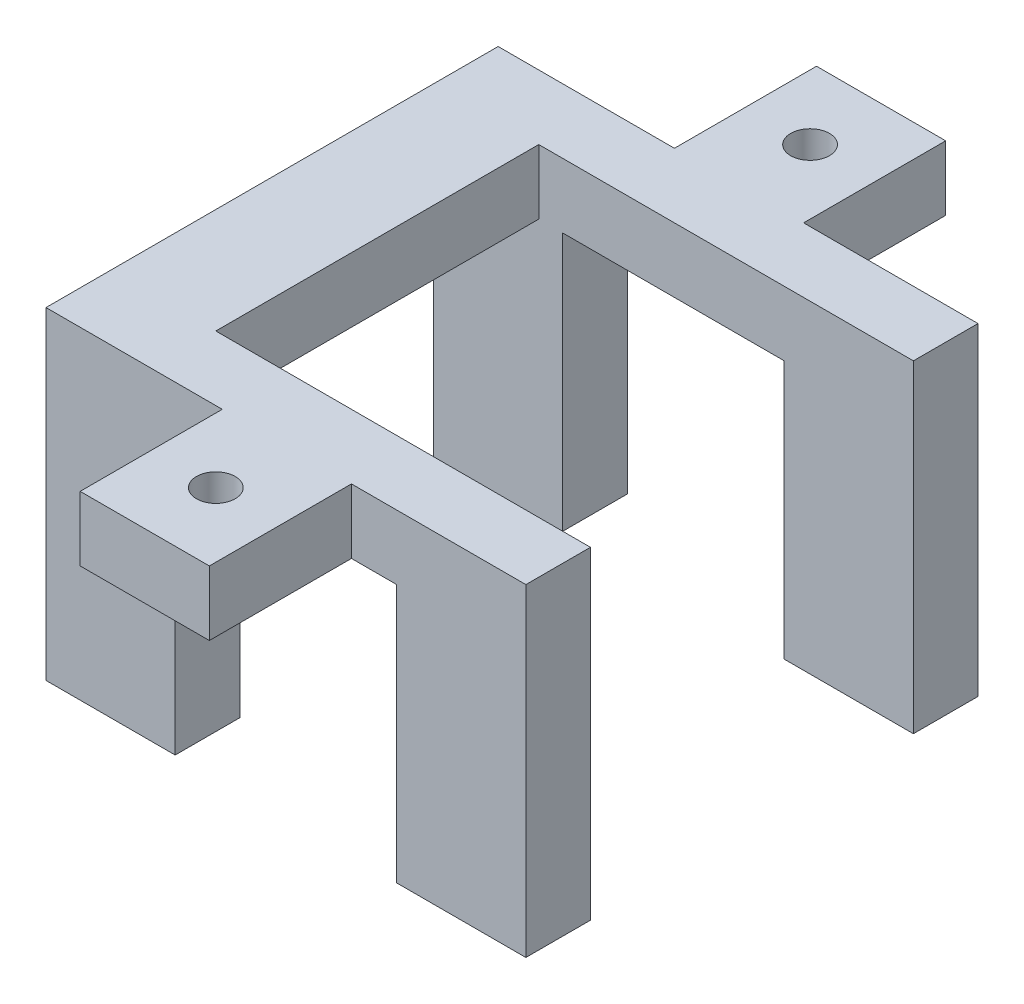
SolidWorks part; units mm, degrees
ref_plane "Front Plane" through (0, 0, 0) normal (0, 0, 1) x (1, 0, 0)
ref_plane "Top Plane" through (0, 0, 0) normal (0, 1, 0) x (1, 0, 0)
ref_plane "Right Plane" through (0, 0, 0) normal (1, 0, 0) x (0, 0, -1)
sketch "Sketch1" plane through (0, 0, 0) normal (0, 1, 0) x (1, 0, 0)
  line L0 (0, 0) -> (0, -2.5)
  line L1 (0, 0) -> (0, 2.5)
  line L3 (0, 0) -> (-1.8324, 0)
  line L5 (1.5, 3) -> (5.5, 3)
  line L6 (5.5, 3) -> (5.5, 0)
  line L7 (5.5, 0) -> (5.5, -3)
  line L8 (5.5, -3) -> (1.5, -3)
  line L10 (0, 4.5) -> (0, 8.5)
  line L11 (0, 8.5) -> (5.5, 8.5)
  line L12 (5.5, 8.5) -> (5.5, 3)
  line L13 (0, -8.5) -> (5.5, -8.5)
  line L14 (5.5, -8.5) -> (5.5, -3)
  line L15 (0, -8.5) -> (0, -4.5)
  line L16 (-1.5, -3) -> (-5.5, -3)
  line L17 (-5.5, -3) -> (-5.5, -8.5)
  line L18 (-5.5, -8.5) -> (0, -8.5)
  line L19 (-5.5, -3) -> (-5.5, 8.5)
  line L20 (-5.5, 8.5) -> (0, 8.5)
  circle A0 centre (0, 3) radius 1.5
  circle A1 centre (0, -3) radius 1.5
extrude "Boss-Extrude1" add sketch "Sketch1" along normal blind 5 contours L19 L20 L11 L12 L6 L7 L14 L13 L18 L17
sketch "Sketch3" plane through (0, 0, 8.5) normal (0, 0, 1) x (1, 0, 0)
  line L0 (-5.5, 5) -> (-5.5, 0)
  line L1 (-5.5, 0) -> (5.5, 0)
  line L2 (5.5, 0) -> (5.5, 5)
  line L3 (5.5, 5) -> (-5.5, 5)
extrude "Boss-Extrude2" add sketch "Sketch3" along normal blind 5
sketch "Sketch4" plane through (5.5, 0, 0) normal (1, 0, 0) x (0, 0, -1)
  line L0 (-13.5, 5) -> (-8.5, 5)
  line L1 (-13.5, 5) -> (8.5, 5) construction
  line L2 (-8.5, 5) -> (-8.5, 0)
  line L3 (8.5, 0) -> (-13.5, 0) construction
  line L4 (-8.5, 0) -> (-13.5, 0)
  line L5 (-13.5, 0) -> (-13.5, 5)
extrude "Boss-Extrude3" add sketch "Sketch4" along normal blind 21
sketch "Sketch5" plane through (0, 0, 0) normal (0, -1, 0) x (1, 0, 0)
  line L0 (26.5, 13.5) -> (16.5, 13.5)
  line L1 (-5.5, 13.5) -> (26.5, 13.5) construction
  line L2 (16.5, 13.5) -> (16.5, 8.5)
  line L3 (26.5, 8.5) -> (5.5, 8.5) construction
  line L4 (16.5, 8.5) -> (26.5, 8.5)
  line L5 (26.5, 8.5) -> (26.5, 13.5)
extrude "Boss-Extrude4" add sketch "Sketch5" along normal blind 20
sketch "Sketch6" plane through (0, 0, -8.5) normal (0, 0, -1) x (-1, 0, 0)
  line L0 (5.5, 5) -> (5.5, 0)
  line L1 (5.5, 0) -> (-5.5, 0)
  line L2 (-5.5, 0) -> (-5.5, 5)
  line L3 (-5.5, 5) -> (5.5, 5)
extrude "Boss-Extrude5" add sketch "Sketch6" along normal blind 5
sketch "Sketch7" plane through (5.5, 0, 0) normal (1, 0, 0) x (0, 0, -1)
  line L0 (13.5, 5) -> (8.5, 5)
  line L1 (-8.5, 5) -> (13.5, 5) construction
  line L2 (8.5, 5) -> (8.5, 0)
  line L3 (13.5, 0) -> (-8.5, 0) construction
  line L4 (8.5, 0) -> (13.5, 0)
  line L5 (13.5, 0) -> (13.5, 5)
extrude "Boss-Extrude6" add sketch "Sketch7" along normal blind 21
sketch "Sketch8" plane through (0, 0, 0) normal (0, -1, 0) x (-1, 0, 0)
  line L0 (-26.5, 8.5) -> (-16.5, 8.5)
  line L1 (-26.5, 8.5) -> (-5.5, 8.5) construction
  line L2 (-16.5, 8.5) -> (-16.5, 13.5)
  line L3 (-26.5, 13.5) -> (5.5, 13.5) construction
  line L4 (-16.5, 13.5) -> (-26.5, 13.5)
  line L5 (-26.5, 13.5) -> (-26.5, 8.5)
extrude "Boss-Extrude7" add sketch "Sketch8" along normal blind 20 contours L2 L4 L5 L0
sketch "Sketch11" plane through (0, 0, 8.5) normal (0, 0, -1) x (-1, 0, 0)
  line L0 (-26.5, -20) -> (-26.5, -15)
  line L1 (-26.5, -20) -> (-26.5, 5) construction
  line L2 (-26.5, -15) -> (-26.5, -10)
  line L3 (-26.5, -10) -> (-16.5, -10)
  line L4 (-16.5, -20) -> (-16.5, 0) construction
  line L5 (-16.5, -10) -> (-16.5, -15)
  line L6 (-16.5, -15) -> (-26.5, -15)
extrude "Boss-Extrude8" add sketch "Sketch11" along normal blind 3.5 contours L2 L3 L5 L6
sketch "Sketch12" plane through (0, 0, -8.5) normal (0, 0, 1) x (1, 0, 0)
  line L0 (26.5, -20) -> (26.5, -15)
  line L1 (26.5, 5) -> (26.5, -20) construction
  line L2 (26.5, -15) -> (26.5, -10)
  line L3 (26.5, -10) -> (16.5, -10)
  line L4 (16.5, -20) -> (16.5, 0) construction
  line L5 (16.5, -10) -> (16.5, -15)
  line L6 (16.5, -15) -> (26.5, -15)
extrude "Boss-Extrude9" add sketch "Sketch12" along normal blind 3.5 contours L2 L3 L5 L6
sketch "Sketch14" plane through (26.5, 0, 0) normal (1, 0, 0) x (0, 0, -1)
  line L4 (-6.3796, -12.8796) -> (-6.3796, -15)
  line L7 (-6.3796, -15) -> (-5, -15)
  line L8 (-6.3796, -12.8796) -> (-6.3796, -11.4398)
  line L10 (-6.3796, -11.4398) -> (-5, -11.4398)
  line L11 (-5, -15) -> (-5, -10) construction
  line L12 (-5, -15) -> (-8.5, -15) construction
  line L13 (-5, -15) -> (-5, -11.4398)
extrude "Cut-Extrude6" cut sketch "Sketch14" against normal blind 14.5 contours L4 L7 L13 L10 L8
sketch "Sketch16" plane through (26.5, 0, 0) normal (1, 0, 0) x (0, 0, -1)
  line L0 (-8.5, -15) -> (-7.4398, -15)
  line L2 (-6.3796, -15) -> (-8.5, -15) construction
  line L3 (-6.3796, -15) -> (-6.3796, -13)
  line L4 (-6.3796, -11.4398) -> (-6.3796, -15) construction
  line L5 (-6.3796, -13) -> (-8.5, -15)
extrude "Cut-Extrude8" cut sketch "Sketch16" against normal blind 14.5 and the other way through all contours L3 L5 L0
sketch "Sketch17" plane through (26.5, 0, 0) normal (1, 0, 0) x (0, 0, -1)
  line L0 (5, -10) -> (5, -11.44)
  line L1 (5, -15) -> (5, -10) construction
  line L2 (5, -11.44) -> (6.38, -11.44)
  line L3 (6.38, -11.44) -> (6.38, -15)
  line L4 (5, -15) -> (8.5, -15) construction
  line L5 (5, -11.44) -> (5, -15)
  line L6 (5, -15) -> (6.38, -15)
extrude "Cut-Extrude9" cut sketch "Sketch17" against normal blind 14.5 contours L2 L3 L6 L5
sketch "Sketch18" plane through (26.5, 0, 0) normal (1, 0, 0) x (0, 0, -1)
  line L0 (6.38, -13) -> (6.38, -15)
  line L1 (6.38, -11.44) -> (6.38, -15) construction
  line L2 (6.38, -13) -> (8.5, -15)
  line L3 (6.38, -15) -> (8.5, -15)
extrude "Cut-Extrude10" cut sketch "Sketch18" against normal blind 14.5 contours L2 L3 L0
sketch "草图1" plane through (0, 0, 13.5) normal (0, 0, 1) x (1, 0, 0)
  line L0 (26.5, 5) -> (34.5, 5)
  line L1 (26.5, 5) -> (26.5, -20)
  line L2 (26.5, -20) -> (34.5, -20)
  line L3 (34.5, -20) -> (34.5, 5)
extrude "凸台-拉伸1" add sketch "草图1" against normal blind 5
sketch "草图2" plane through (0, 0, -13.5) normal (0, 0, -1) x (-1, 0, 0)
  line L0 (-26.5, -20) -> (-34.5, -20)
  line L1 (-34.5, -20) -> (-34.5, 5)
  line L2 (-34.5, 5) -> (-26.5, 5)
  line L3 (-26.5, 5) -> (-26.5, -20)
extrude "凸台-拉伸2" add sketch "草图2" against normal blind 5
sketch "草图3" plane through (0, 0, 13.5) normal (0, 0, 1) x (1, 0, 0)
  line L0 (16.5, -20) -> (16.5, -15)
sketch "草图4" plane through (0, 0, 8.5) normal (0, 0, -1) x (-1, 0, 0)
  line L7 (-22.5, 5) -> (-22.5, 0.9274) construction
  line L8 (-22.5, 5) -> (-22.5, 3.9274) construction
  line L9 (-22.5, 3.9274) -> (-22.5, 3.0274)
  line L10 (-5.5, 5) -> (-34.5, 5)
  line L11 (-34.5, 5) -> (-34.5, -20)
  line L12 (-34.5, -20) -> (-16.5, -20)
  line L13 (-16.5, -20) -> (-16.5, -15)
  line L14 (-16.5, -15) -> (-26.5, -15)
  line L15 (-26.5, -15) -> (-26.5, -10)
  line L16 (-26.5, -10) -> (-16.5, -10)
  line L17 (-16.5, -10) -> (-16.5, 0)
  line L18 (-16.5, 0) -> (-5.5, 0)
  line L19 (-5.5, 0) -> (-5.5, 5)
  line L20 (-5.5, 5) -> (-34.5, 5) construction
  line L21 (-34.5, 5) -> (-34.5, -20) construction
  line L22 (-34.5, -20) -> (-16.5, -20) construction
  line L23 (-16.5, -20) -> (-16.5, -15) construction
  line L24 (-16.5, -15) -> (-26.5, -15) construction
  line L25 (-26.5, -15) -> (-26.5, -10) construction
  line L26 (-26.5, -10) -> (-16.5, -10) construction
  line L27 (-16.5, -10) -> (-16.5, 0) construction
  line L28 (-16.5, 0) -> (-5.5, 0) construction
  line L29 (-5.5, 0) -> (-5.5, 5) construction
  line L30 (-23.4, 3.0274) -> (-23.4, 0.0274)
  line L31 (-23.4, 0.0274) -> (-22.5, 0.0274)
  line L32 (-21.6, 0.0274) -> (-21.6, 3.0274)
  line L33 (-22.5, 0.0274) -> (-22.5, -9.8364) construction
  arc A0 (-21.6, 3.0274) -> (-23.4, 3.0274) centre (-22.5, 3.0274) ccw
  arc A1 (-23.4, 0.0274) -> (-21.6, 0.0274) centre (-22.5, 0.0274) ccw
  dimension "D1" = 0
sketch "草图6" plane through (0, 0, -8.5) normal (0, 0, 1) x (1, 0, 0)
  line L5 (21.5, 3.1) -> (21.5, 0.1)
  line L6 (23.3, 3.1) -> (23.3, 0.1)
  line L10 (16.5, -10) -> (26.5, -10)
  line L11 (26.5, -10) -> (26.5, -15)
  line L14 (26.5, -15) -> (16.5, -15)
  line L15 (26.5, -15) -> (16.5, -15)
  line L16 (34.5, 5) -> (5.5, 5)
  line L17 (5.5, 5) -> (5.5, 0)
  line L18 (5.5, 0) -> (16.5, 0)
  line L19 (16.5, 0) -> (16.5, -10)
  line L20 (16.5, -10) -> (26.5, -10) construction
  line L21 (26.5, -10) -> (26.5, -15) construction
  line L26 (34.5, 5) -> (5.5, 5) construction
  line L27 (5.5, 5) -> (5.5, 0) construction
  line L28 (5.5, 0) -> (16.5, 0) construction
  line L29 (16.5, 0) -> (16.5, -10) construction
  line L30 (16.5, -15) -> (16.5, -20)
  line L31 (16.5, -15) -> (16.5, -20)
  line L32 (16.5, -20) -> (34.5, -20)
  line L33 (16.5, -20) -> (34.5, -20)
  line L34 (34.5, -20) -> (34.5, 5)
  line L35 (34.5, -20) -> (34.5, 5)
  arc A1 (23.3, 3.1) -> (21.5, 3.1) centre (22.4, 3.1) ccw
  arc A2 (21.5, 0.1) -> (23.3, 0.1) centre (22.4, 0.1) ccw
  dimension "D1" = 0
sketch "Skizze1" plane through (0, 5, 0) normal (0, 1, 0) x (1, 0, 0)
  line L0 (0, 13.5) -> (0, 5.5)
  line L2 (-5.5, 13.5) -> (34.5, 13.5) construction
  line L3 (0, -13.5) -> (0, -5.5)
  line L4 (34.5, -13.5) -> (-5.5, -13.5) construction
  circle A0 centre (-0.0269, -4.0002) radius 1.5
  circle A1 centre (0.0725, 4.0018) radius 1.5
sketch "Skizze2" plane through (0, 0, 13.5) normal (0, 0, 1) x (1, 0, 0)
  line L0 (-5.5, 5) -> (-5.5, 0)
  line L1 (-5.5, 0) -> (16.5, 0)
  line L2 (16.5, 0) -> (16.5, -20)
  line L3 (16.5, -20) -> (34.5, -20)
  line L4 (34.5, -20) -> (34.5, 5)
  line L5 (34.5, 5) -> (-5.5, 5)
extrude "Aufsatz-Linear austragen1" add sketch "Skizze2" along normal blind 4
sketch "Skizze3" plane through (0, 0, 5) normal (0, 0, -1) x (-1, 0, 0)
  line L0 (-26.5, -10) -> (-26.5, -15)
  line L1 (-26.5, -15) -> (-16.5, -15)
  line L2 (-16.5, -15) -> (-16.5, -10)
  line L3 (-16.5, -10) -> (-26.5, -10)
extrude "Schnitt-Linear austragen2" cut sketch "Skizze3" against normal blind 3.5
sketch "Skizze4" plane through (0, 0, 8.5) normal (0, 0, -1) x (-1, 0, 0)
  line L0 (-34.5, 5) -> (-34.5, -20)
  line L1 (-34.5, -20) -> (-16.5, -20)
  line L2 (-16.5, -20) -> (-16.5, 0)
  line L3 (-16.5, 0) -> (-5.5, 0)
  line L4 (-5.5, 0) -> (-5.5, 5)
  line L5 (-5.5, 5) -> (-34.5, 5)
extrude "Schnitt-Linear austragen3" cut sketch "Skizze4" against normal blind 4
sketch "Skizze6" plane through (0, 0, 17.5) normal (0, 0, 1) x (1, 0, 0)
  line L0 (-5.5, 5) -> (5.5, 5)
  line L1 (34.5, 5) -> (-5.5, 5) construction
  line L2 (11, 5) -> (21, 5)
  line L3 (16, 5) -> (11, 5)
  line L4 (16, 5) -> (21, 5)
  line L5 (11, 5) -> (11, 0)
  line L6 (-5.5, 0) -> (16.5, 0) construction
  line L7 (11, 0) -> (21, 0)
  line L8 (21, 0) -> (21, 5)
  line M1 (34.5, 5) -> (-5.5, 5)
  line M3 (-5.5, 0) -> (16.5, 0)
extrude "Aufsatz-Linear austragen3" add sketch "Skizze6" along normal blind 11 contours L7 L8 L2 L5 M1 M3
sketch "Skizze7" plane through (0, 5, 0) normal (0, 1, 0) x (1, 0, 0)
  circle A0 centre (16, -23) radius 1.5
  circle A1 centre (16, -23) radius 3.5
extrude "Schnitt-Linear austragen6" cut sketch "Skizze7" against normal blind 10 contours A0
sketch "Skizze8" plane through (0, 0, -8.5) normal (0, 0, 1) x (1, 0, 0)
  line L0 (16.5, -10) -> (16.5, -15)
  line L1 (16.5, -15) -> (26.5, -15)
  line L2 (26.5, -15) -> (26.5, -10)
  line L3 (26.5, -10) -> (16.5, -10)
extrude "Schnitt-Linear austragen8" cut sketch "Skizze8" along normal blind 4
sketch "Skizze9" plane through (0, 0, -13.5) normal (0, 0, -1) x (-1, 0, 0)
  line L0 (-34.5, 5) -> (-34.5, -20)
  line L1 (-34.5, -20) -> (-16.5, -20)
  line L2 (-16.5, -20) -> (-16.5, 0)
  line L3 (-16.5, 0) -> (5.5, 0)
  line L4 (5.5, 0) -> (5.5, 5)
  line L5 (5.5, 5) -> (-34.5, 5)
extrude "Aufsatz-Linear austragen4" add sketch "Skizze9" along normal blind 4
sketch "Skizze10" plane through (0, 0, -8.5) normal (0, 0, 1) x (1, 0, 0)
  line L0 (5.5, 5) -> (5.5, 0)
  line L1 (5.5, 0) -> (16.5, 0)
  line L2 (16.5, 0) -> (16.5, -20)
  line L3 (16.5, -20) -> (34.5, -20)
  line L4 (34.5, -20) -> (34.5, 5)
  line L5 (34.5, 5) -> (5.5, 5)
extrude "Schnitt-Linear austragen9" cut sketch "Skizze10" against normal blind 4
sketch "Skizze11" plane through (0, 0, -17.5) normal (0, 0, -1) x (-1, 0, 0)
  line L0 (5.5, 5) -> (-6.249, 5)
  line L1 (5.5, 5) -> (-34.5, 5) construction
  line L2 (-11, 5) -> (-21, 5)
  line L12 (5.5, 5) -> (-11, 5)
  line L13 (-21, 5) -> (-21, 0)
  line L14 (-21, 0) -> (-11, 0)
  line L15 (-11, 0) -> (-11, 5)
  line M1 (5.5, 5) -> (-34.5, 5)
  line M5 (-16.5, 0) -> (5.5, 0)
extrude "Aufsatz-Linear austragen6" add sketch "Skizze11" along normal blind 11 contours L15 L13 L14 M5 M1
sketch "Skizze12" plane through (0, 5, 0) normal (0, 1, 0) x (1, 0, 0)
  circle A0 centre (16, 23) radius 1.5
  circle A1 centre (16, 23) radius 3.5
extrude "Schnitt-Linear austragen10" cut sketch "Skizze12" against normal blind 11 contours A0
sketch "Skizze15" plane through (0, 0, 17.5) normal (0, 0, 1) x (1, 0, 0)
  line L0 (34.5, 0) -> (24.5, 0)
  line L1 (34.5, -20) -> (34.5, 5) construction
  line L2 (24.5, 0) -> (24.5, -20)
  line L3 (16.5, -20) -> (34.5, -20) construction
  line L4 (24.5, -20) -> (16.5, -20)
  line L5 (16.5, -20) -> (16.5, 0)
  line L6 (16.5, 0) -> (24.5, 0)
extrude "Schnitt-Linear austragen11" cut sketch "Skizze15" against normal blind 37 contours L2 L4 L5 L6
sketch "Skizze16" plane through (0, 0, 0) normal (0, -1, 0) x (1, 0, 0)
  line L0 (11, 17.5) -> (7.3552, 17.5)
  line L1 (-5.5, 17.5) -> (11, 17.5) construction
  line L2 (7.3552, 17.5) -> (7.3552, 12.5)
  line L3 (24.5, 12.5) -> (5.5, 12.5) construction
  line L5 (7.3552, 17.5) -> (-2.6448, 17.5)
  line L6 (-2.6448, 17.5) -> (-2.6448, 12.5)
  line L7 (-2.6448, 12.5) -> (7.3552, 12.5)
  line M1 (5.5, 12.5) -> (24.5, 12.5)
  line M7 (11, 17.5) -> (-5.5, 17.5)
extrude "Aufsatz-Linear austragen7" add sketch "Skizze16" along normal blind 20 contours L6 L7 L2 M1 M7
sketch "Skizze17" plane through (0, 0, 0) normal (0, -1, 0) x (1, 0, 0)
  line L0 (-2.6448, 12.5) -> (-2.6448, -17.5)
  line L1 (11, -17.5) -> (-5.5, -17.5) construction
  line L2 (-2.6448, -17.5) -> (7.3552, -17.5)
  line L3 (7.3552, -17.5) -> (7.3552, -12.5)
  line L4 (5.5, -12.5) -> (24.5, -12.5) construction
  line L5 (7.3552, -12.5) -> (-2.6448, -12.5)
  line M5 (-5.5, -17.5) -> (11, -17.5)
  line M11 (24.5, -12.5) -> (5.5, -12.5)
extrude "Aufsatz-Linear austragen8" add sketch "Skizze17" along normal blind 20 contours L5 L0 L3 M11 M5
sketch "Skizze18" plane through (0, 0, -17.5) normal (0, 0, -1) x (-1, 0, 0)
  line L0 (5.5, 5) -> (5.5, 0)
  line L1 (5.5, 0) -> (2.6448, 0)
  line L2 (2.6448, 0) -> (2.6448, 5)
  line L3 (5.5, 5) -> (-11, 5) construction
  line L4 (2.6448, 5) -> (5.5, 5)
extrude "Schnitt-Linear austragen12" cut sketch "Skizze18" against normal blind 35
